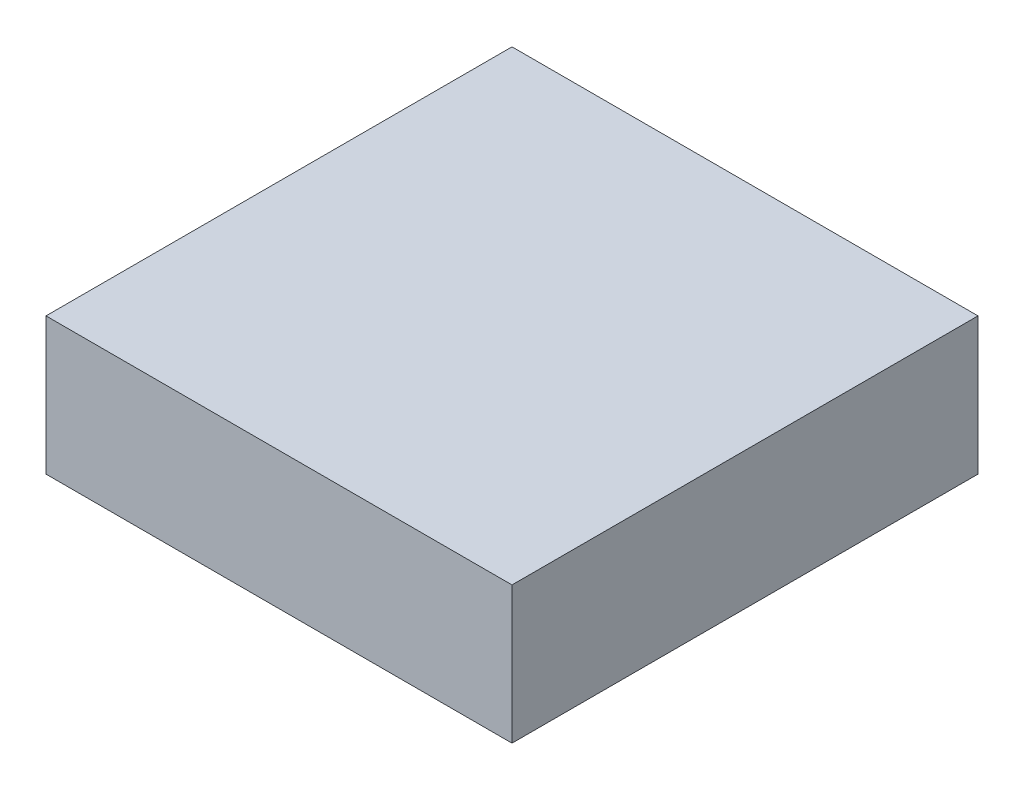
SolidWorks part; units mm, degrees
ref_plane "Front Plane" through (0, 0, 0) normal (0, 0, 1) x (1, 0, 0)
ref_plane "Top Plane" through (0, 0, 0) normal (0, 1, 0) x (1, 0, 0)
ref_plane "Right Plane" through (0, 0, 0) normal (1, 0, 0) x (0, 0, -1)
sketch "Sketch2" plane through (0, 0, 0) normal (0, 1, 0) x (1, 0, 0)
  line L1 (0, 0) -> (431.8, 0)
  line L2 (0, 0) -> (0, 431.8)
  line L3 (0, 431.8) -> (431.8, 431.8)
  line L4 (431.8, 0) -> (431.8, 431.8)
  dimension "D1" = 431.8
extrude "Boss-Extrude1" add sketch "Sketch2" along normal blind 127
